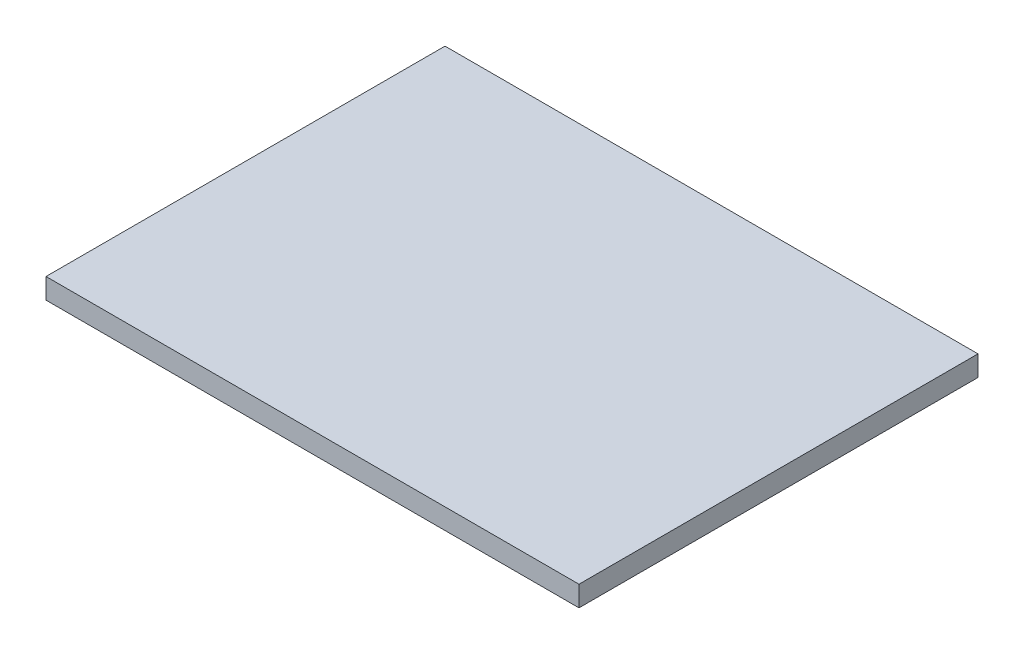
SolidWorks part; units mm, degrees
ref_plane "Front Plane" through (0, 0, 0) normal (0, 0, 1) x (1, 0, 0)
ref_plane "Top Plane" through (0, 0, 0) normal (0, 1, 0) x (1, 0, 0)
ref_plane "Right Plane" through (0, 0, 0) normal (1, 0, 0) x (0, 0, -1)
sketch "Sketch1" plane through (0, 0, 0) normal (0, 1, 0) x (1, 0, 0)
  line L1 (-130, -97.3186) -> (130, -97.3186)
  line L2 (-130, -97.3186) -> (-130, 97.3186)
  line L3 (-130, 97.3186) -> (130, 97.3186)
  line L4 (130, -97.3186) -> (130, 97.3186)
  line L5 (-130, -97.3186) -> (130, 97.3186) construction
  line L6 (-130, 97.3186) -> (130, -97.3186) construction
  point P0 (0, 0)
extrude "Boss-Extrude1" add sketch "Sketch1" along normal blind 10
